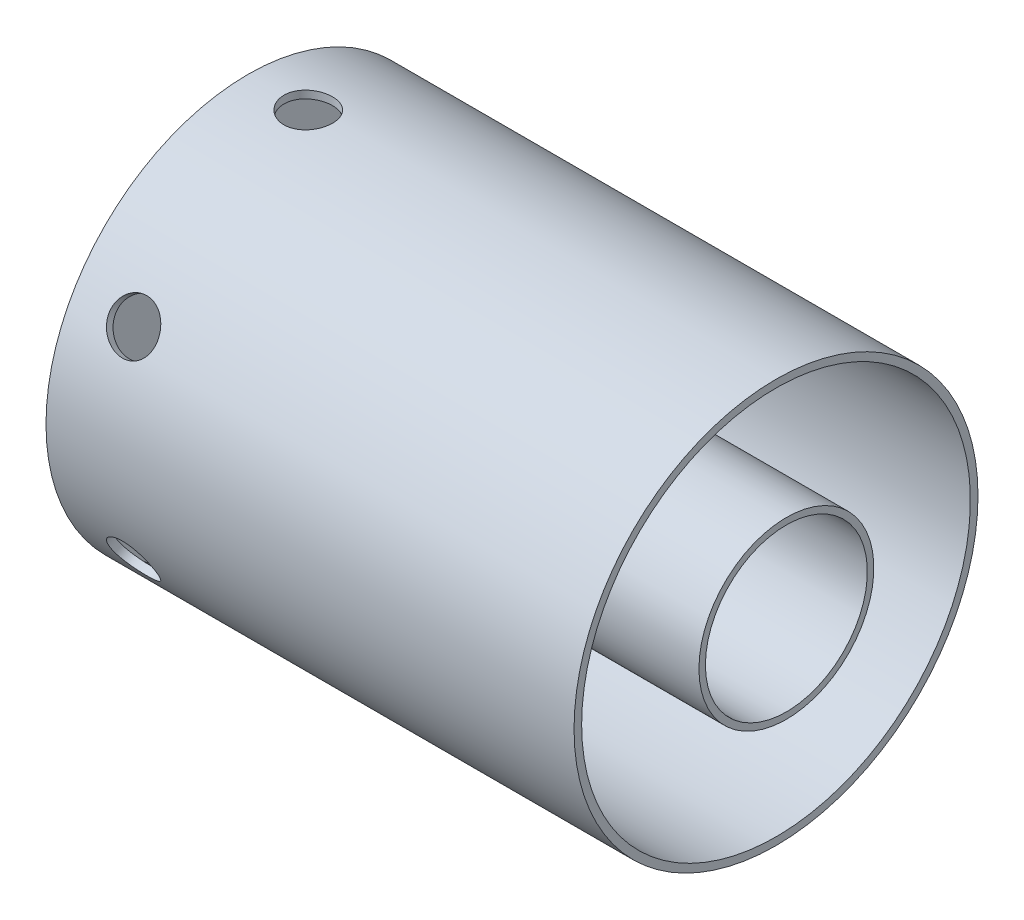
SolidWorks part; units mm, degrees
ref_plane "Front Plane" through (0, 0, 0) normal (0, 0, 1) x (1, 0, 0)
ref_plane "Top Plane" through (0, 0, 0) normal (0, 1, 0) x (1, 0, 0)
ref_plane "Right Plane" through (0, 0, 0) normal (1, 0, 0) x (0, 0, -1)
sketch "Sketch2" plane through (0, 0, 0) normal (0, 0, 1) x (1, 0, 0)
  line L0 (0.0787, 31.75) -> (0.0787, 79.1845)
  line L1 (0.0787, 79.1845) -> (207.0887, 79.1845)
  line L2 (5.1629, 76.2) -> (5.1629, 34.29)
  line L3 (5.1629, 76.2) -> (207.0887, 76.2)
  line L4 (5.1629, 34.29) -> (127, 34.29)
  line L5 (207.0887, 79.1845) -> (207.0887, 76.2)
  line L8 (211.1527, 34.29) -> (211.1527, 31.75)
  line L15 (0.0787, 31.75) -> (211.1527, 31.75)
  line L20 (0, 0) -> (168.8359, 0)
  line L25 (127, 34.29) -> (211.1527, 34.29)
  dimension "D1" = 2.54
  dimension "D2" = 207.01
  dimension "D3" = 76.2
  dimension "D4" = 2.9845
  dimension "D5" = 31.75
  dimension "D6" = 211.074
revolve "Revolve2" add sketch "Sketch2" angle 360 about L20
ref_plane "Plane1" through (0, 79.1845, 0) normal (0, 1, 0) x (1, 0, 0)
ref_plane "Plane2" through (0, -79.1845, 0) normal (0, 1, 0) x (1, 0, 0)
sketch "Sketch9" plane through (0, 79.1845, 0) normal (0, 1, 0) x (1, 0, 0)
  line L0 (0, 0) -> (168.8359, 0) construction
  circle A0 centre (23.7189, 0) radius 9.525
sketch "Sketch10" plane through (0, -79.1845, 0) normal (0, 1, 0) x (1, 0, 0)
  circle A0 centre (23.7189, 0) radius 9.525
extrude "Cut-Extrude9" cut sketch "Sketch9" against normal blind 5.842 contours A0
extrude "Cut-Extrude10" cut sketch "Sketch10" along normal blind 66.04 contours A0
pattern_circular "CirPattern1" count 3 every 120 about axis through (0, 0, 0) along (-1, 0, 0) of "Cut-Extrude9"
pattern_circular "CirPattern2" count 3 every 120 about axis through (0, 0, 0) along (-1, 0, 0) of "Cut-Extrude10"
